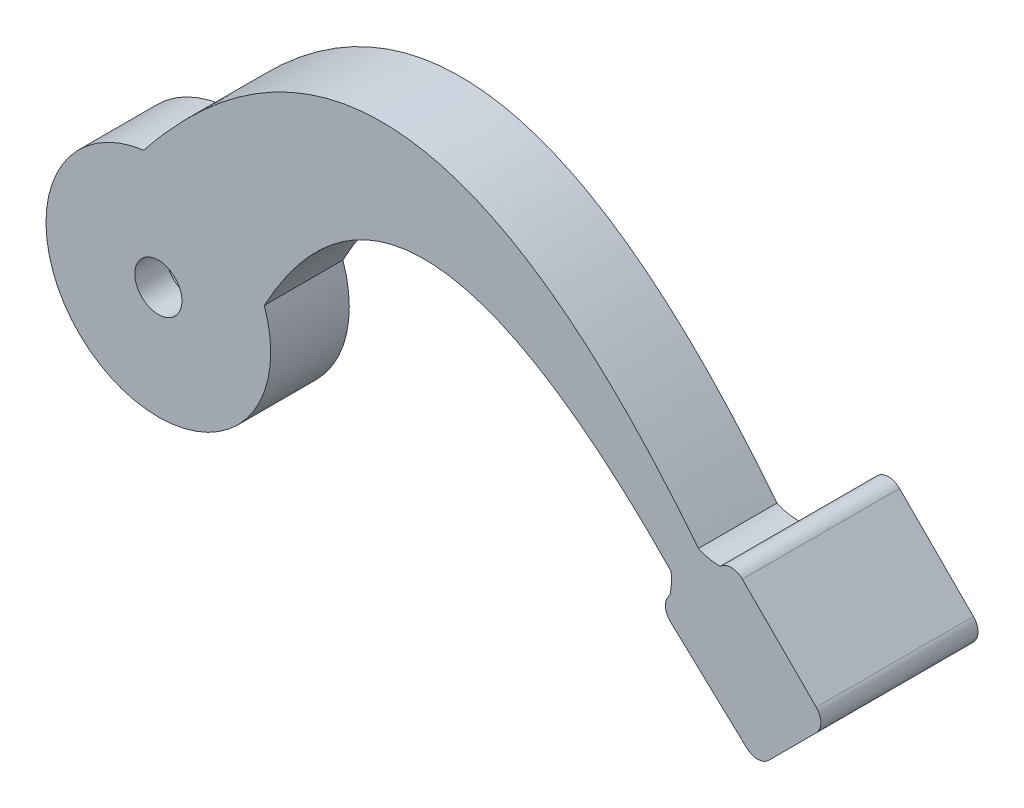
SolidWorks part; units mm, degrees
ref_plane "Plan de face" through (0, 0, 0) normal (0, 0, 1) x (1, 0, 0)
ref_plane "Plan de dessus" through (0, 0, 0) normal (0, 1, 0) x (1, 0, 0)
ref_plane "Plan de droite" through (0, 0, 0) normal (1, 0, 0) x (0, 0, -1)
sketch "Esquisse1" plane through (0, 0, 0) normal (0, 0, 1) x (1, 0, 0)
  circle A0 centre (0, 0) radius 3.15
  circle A1 centre (0, 0) radius 7.15
  dimension "D1" = 6.3
  dimension "D2" = 4
extrude "Boss.-Extru.1" add sketch "Esquisse1" along normal blind 5
sketch "Esquisse2" plane through (0, 0, 5) normal (0, 0, 1) x (1, 0, 0)
  line L1 (-0.9268, 7.0897) -> (6.7439, 2.3754)
  line L2 (35.9052, 0.7602) -> (34.0211, -0.8243) construction
  line L3 (35.9052, 0.7602) -> (36.0732, -1.352) construction
  line L4 (34.0211, -0.8243) -> (36.0732, -1.352) construction
  circle A0 centre (0, 0) radius 7.15 construction
  spline S0 degree 2 poles (-0.9268, 7.0897) (15.7376, 28.1144) (35.9052, 0.7602) knots 0 0 0 1 1 1
  spline S1 degree 2 poles (34.0211, -0.8243) (15.7783, 19.1171) (6.7439, 2.3754) knots 0 0 0 1 1 1
  spline S2 degree 2 poles (35.9052, 0.7602) (37.1832, -2.6719) (34.0211, -0.8243) knots 0 0 0 1 1 1
  point P5 (34.0211, -0.8243)
  point P9 (0, 0)
  point P12 (0, 0)
  point P13 (36.0732, -1.352)
  point P14 (11.6637, 8.3356)
  dimension "D1" = 37
  dimension "D2" = 2.4619
extrude "Boss.-Extru.2" add sketch "Esquisse2" against normal blind 5
sketch "Esquisse3" plane through (0, 0, 5) normal (0, 0, 1) x (1, 0, 0)
  circle A0 centre (0, 0) radius 1.5
  circle A1 centre (0, 0) radius 3.15
  dimension "D1" = 3
extrude "Boss.-Extru.3" add sketch "Esquisse3" against normal blind 2
ref_plane "Plan1" through (27, 0, 0) normal (1, 0, 0) x (0, 0, -1)
sketch "Esquisse6" plane through (0, 0, 5) normal (0, 0, 1) x (1, 0, 0)
  line L1 (37.1622, 2.4958) -> (41.8638, -2.2058)
  line L2 (41.8638, -3.6201) -> (38.8375, -6.6464)
  line L3 (37.4487, -6.671) -> (32.5805, -2.1359)
  line L4 (31.3681, 3.2406) -> (32.9214, 4.0172)
  arc A0 (35.748, 2.4958) -> (37.1622, 2.4958) centre (36.4551, 1.7887) cw
  arc A1 (41.8638, -2.2058) -> (41.8638, -3.6201) centre (41.1567, -2.9129) cw
  arc A2 (38.8375, -6.6464) -> (37.4487, -6.671) centre (38.1304, -5.9393) cw
  arc A3 (32.555, -0.6971) -> (32.5805, -2.1359) centre (33.2622, -1.4042) ccw
  parabola Q0 (35.9052, 0.7602) -> (-0.9268, 7.0897) focus (13.7265, 9.4254) apex (13.2366, 16.1912) construction
  parabola Q1 (6.7439, 2.3754) -> (34.0211, -0.8243) focus (15.7803, 5.5227) apex (14.7193, 9.7497) construction
  spline S0 degree 2 poles (35.748, 2.4958) (33.9749, 2.5251) (32.9214, 4.0172) knots 0 0 0 1 1 1
  spline S1 degree 2 poles (32.555, -0.6971) (33.0113, 1.4833) (31.3681, 3.2406) knots 0 0 0 1 1 1
  dimension "D1" = 1
extrude "Boss.-Extru.5" add sketch "Esquisse6" against normal blind 10
sketch "Esquisse7" plane through (0, 0, -5) normal (0, 0, -1) x (-1, 0, 0)
  line L0 (-35.748, 2.4958) -> (-32.555, -0.6971)
  line L1 (-32.555, -0.6971) -> (-29.6172, 2.2407)
  line L2 (-29.6172, 2.2407) -> (-34.4277, 5.5905)
  line L3 (-34.4277, 5.5905) -> (-35.748, 2.4958)
extrude "Enlèv. mat.-Extru.1" cut sketch "Esquisse7" against normal up to surface (5 mm away) up to face at (22.5396, 1.4551, 0)
